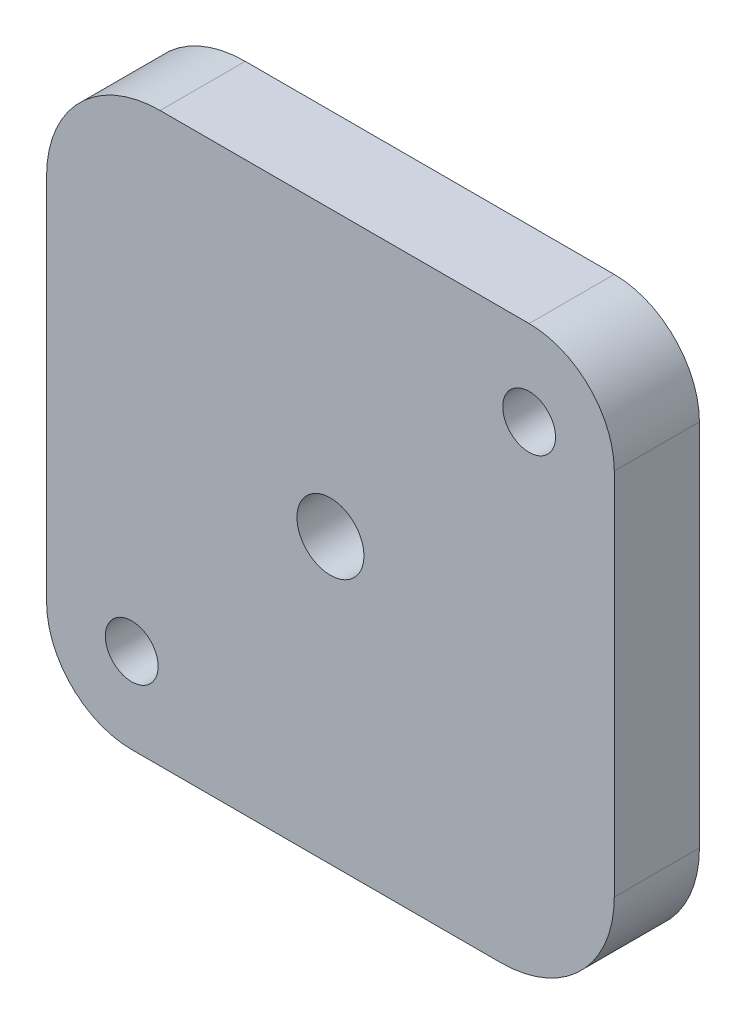
SolidWorks part; units mm, degrees
ref_plane "Front Plane" through (0, 0, 0) normal (0, 0, 1) x (1, 0, 0)
ref_plane "Top Plane" through (0, 0, 0) normal (0, 1, 0) x (1, 0, 0)
ref_plane "Right Plane" through (0, 0, 0) normal (1, 0, 0) x (0, 0, -1)
sketch "Sketch1" plane through (0, 0, 0) normal (0, 0, 1) x (1, 0, 0)
  line L1 (50, 50) -> (-50, 50)
  line L2 (50, 50) -> (50, -50)
  line L3 (50, -50) -> (-50, -50)
  line L4 (-50, 50) -> (-50, -50)
  line L5 (50, 50) -> (-50, -50) construction
  line L6 (50, -50) -> (-50, 50) construction
  point P0 (0, 0)
  dimension "D1" = 100
  dimension "D2" = 100
extrude "Boss-Extrude1" add sketch "Sketch1" along normal blind 15
sketch "Sketch2" plane through (0, 0, 15) normal (0, 0, 1) x (1, 0, 0)
  line L0 (50, -50) -> (50, 50) construction
  line L1 (-50, 50) -> (50, -50) construction
  line L2 (50, 50) -> (-50, 50) construction
  circle A0 centre (35, 35) radius 4.65
  circle A1 centre (-35, -35) radius 4.65
  dimension "D1" = 9.3
  dimension "D2" = 15
  dimension "D3" = 15
extrude "Cut-Extrude1" cut sketch "Sketch2" against normal through all
sketch "Sketch10" plane through (0, 0, 15) normal (0, 0, 1) x (1, 0, 0)
  circle A0 centre (0, 0) radius 5.9
  dimension "D1" = 11.8
extrude "Cut-Extrude5" cut sketch "Sketch10" against normal through all
fillet "Fillet1" radius 20 2 edges at (-50, 50, 7.5) (50, -50, 7.5)
fillet "Fillet2" radius 15 2 edges at (-50, -50, 7.5) (50, 50, 7.5)
